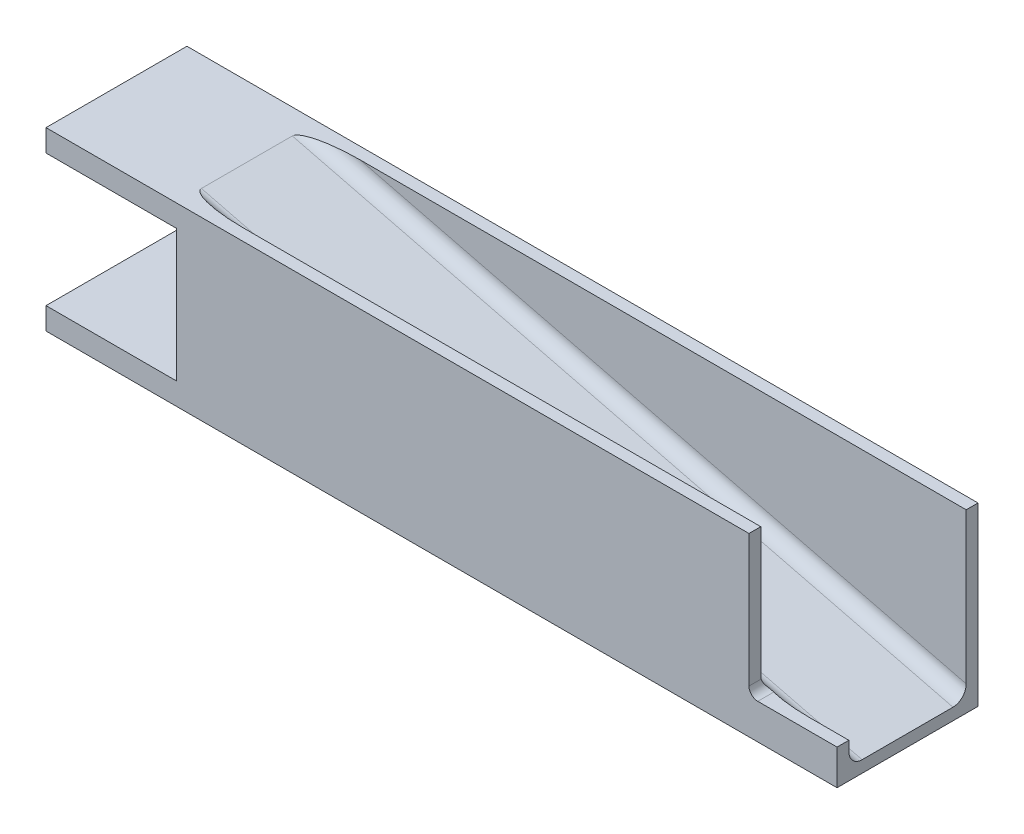
SolidWorks part; units mm, degrees
ref_plane "Front Plane" through (0, 0, 0) normal (0, 0, 1) x (1, 0, 0)
ref_plane "Top Plane" through (0, 0, 0) normal (0, 1, 0) x (1, 0, 0)
ref_plane "Right Plane" through (0, 0, 0) normal (1, 0, 0) x (0, 0, -1)
sketch "Sketch1" plane through (0, 0, 0) normal (0, 1, 0) x (1, 0, 0)
  line L1 (0, 0) -> (190.5, 0)
  line L2 (0, 0) -> (0, 40.64)
  line L3 (0, 40.64) -> (190.5, 40.64)
  line L4 (190.5, 0) -> (190.5, 40.64)
  dimension "D1" = 190.5
  dimension "D2" = 40.64
extrude "Boss-Extrude1" add sketch "Sketch1" along normal blind 50.8
sketch "Sketch2" plane through (190.5, 0, 0) normal (1, 0, 0) x (0, 0, -1)
  line L0 (0, 50.8) -> (0, 0) construction
  line L1 (3.4036, 3.4036) -> (37.2364, 3.4036)
  line L2 (3.4036, 3.4036) -> (3.4036, 56.8897)
  line L3 (3.4036, 56.8897) -> (37.2364, 56.8897)
  line L4 (37.2364, 3.4036) -> (37.2364, 56.8897)
  line L5 (40.64, 50.8) -> (40.64, 0) construction
  line L6 (0, 0) -> (40.64, 0) construction
  line L7 (0, 50.8) -> (40.64, 50.8) construction
  dimension "D1" = 3.4036
  dimension "D2" = 3.4036
  dimension "D3" = 3.4036
  dimension "D4" = 6.0897
extrude "Cut-Extrude1" cut sketch "Sketch2" against normal through all
ref_plane "Plane2" through (11.9023, 47.8387, 0) normal (0.2414, 0.9704, 0) x (0.9704, -0.2414, 0)
sketch "Sketch4" plane through (11.9023, 47.8387, 0) normal (0.2414, 0.9704, 0) x (0.9704, -0.2414, 0)
  line L5 (-12.2651, 37.2364) -> (184.0425, 37.2364)
  line L6 (-12.2651, 37.2364) -> (-12.2651, 3.4036)
  line L7 (-12.2651, 3.4036) -> (184.0425, 3.4036)
  line L8 (184.0425, 37.2364) -> (184.0425, 3.4036)
extrude "Boss-Extrude2" add sketch "Sketch4" against normal up to surface up to face at (95.25, 3.4036, -20.32)
sketch "Sketch6" plane through (0, 0, 0) normal (0, 0, 1) x (1, 0, 0)
  line L0 (0, 50.8) -> (190.5, 50.8) construction
  line L1 (0, 0) -> (-25.4, 0)
  line L2 (0, 0) -> (0, 50.8)
  line L3 (0, 50.8) -> (-25.4, 50.8)
  line L4 (-25.4, 0) -> (-25.4, 50.8)
  dimension "D1" = 0
  dimension "D2" = 25.4
extrude "Cut-Extrude3" cut sketch "Sketch6" against normal through all
fillet "Fillet1" radius 3.81 2 edges at (95.25, 27.1018, -37.2364) (95.25, 27.1018, -3.4036)
sketch "Sketch7" plane through (0, 0, 0) normal (0, 0, 1) x (1, 0, 0)
  line L0 (190.5, 10.16) -> (165.1, 10.16)
  line L1 (190.5, 50.8) -> (190.5, 0) construction
  line L2 (0, 0) -> (190.5, 0) construction
  line L3 (165.1, 10.16) -> (165.1, 50.8)
  line L4 (0, 50.8) -> (190.5, 50.8) construction
  line L5 (165.1, 50.8) -> (190.5, 50.8)
  line L6 (190.5, 50.8) -> (190.5, 10.16)
  dimension "D1" = 25.4
  dimension "D2" = 10.16
extrude "Cut-Extrude4" cut sketch "Sketch7" against normal blind 5.08
sketch "Sketch8" plane through (0, 0, 0) normal (-1, 0, 0) x (0, 0, 1)
  line L1 (-40.64, 50.8) -> (0, 50.8)
  line L2 (-40.64, 50.8) -> (-40.64, 0)
  line L3 (-40.64, 0) -> (0, 0)
  line L4 (0, 50.8) -> (0, 0)
extrude "Boss-Extrude3" add sketch "Sketch8" along normal blind 37.592
fillet "Fillet2" radius 2.54 1 edges at (165.1, 10.16, -2.54)
sketch "Sketch9" plane through (0, 0, 0) normal (0, 0, 1) x (1, 0, 0)
  line L0 (0, 50.8) -> (0, 0)
  line L1 (-37.592, 50.8) -> (165.1, 50.8) construction
  line L2 (-37.592, 0) -> (-37.592, 50.8) construction
  line L3 (-37.592, 6.35) -> (0, 6.35)
  line L4 (-37.592, 6.35) -> (-37.592, 44.45)
  line L5 (-37.592, 44.45) -> (0, 44.45)
  line L6 (0, 6.35) -> (0, 44.45)
  line L7 (-37.592, 0) -> (190.5, 0) construction
  line M10 (-37.592, 50.8) -> (-37.592, 0)
  dimension "D1" = 6.35
  dimension "D2" = 6.35
extrude "Cut-Extrude5" cut sketch "Sketch9" against normal through all contours L5 L3 L0 M10
